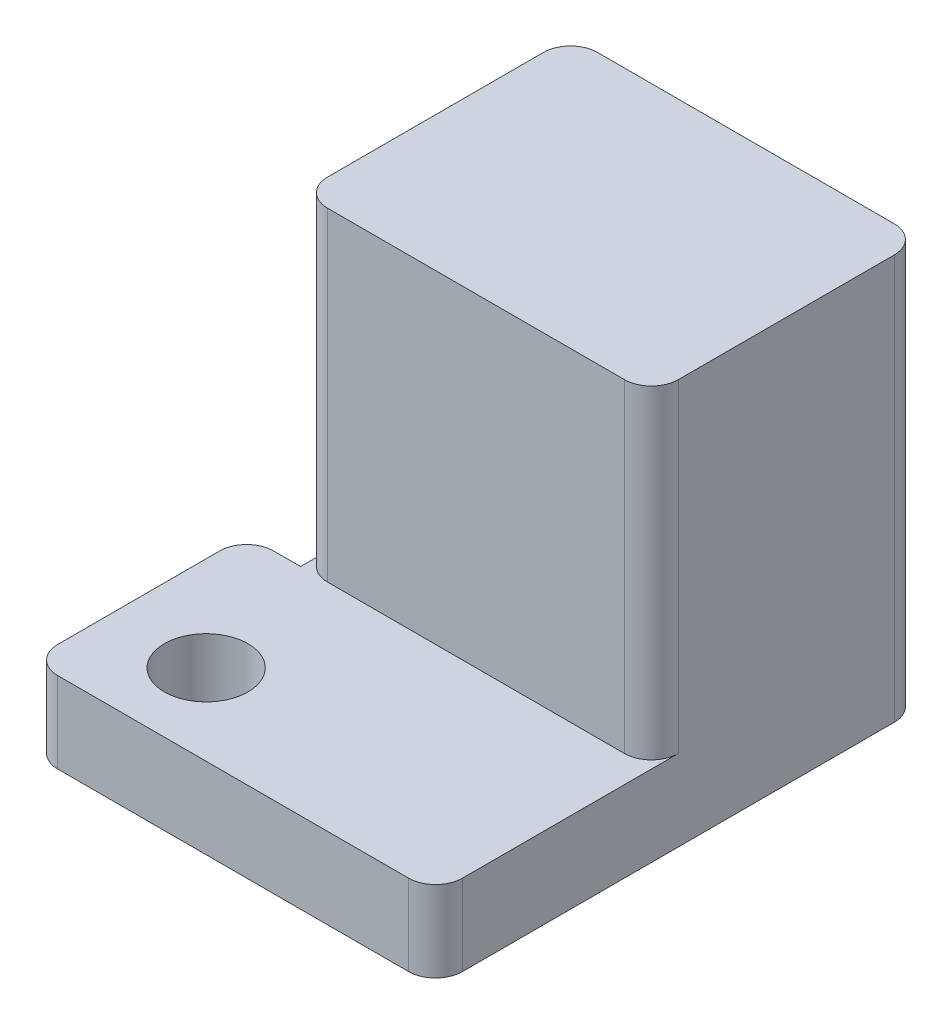
SolidWorks part; units mm, degrees
ref_plane "Alzado" through (0, 0, 0) normal (0, 0, 1) x (1, 0, 0)
ref_plane "Planta" through (0, 0, 0) normal (0, 1, 0) x (1, 0, 0)
ref_plane "Vista lateral" through (0, 0, 0) normal (1, 0, 0) x (0, 0, -1)
sketch "Croquis1" plane through (0, 0, 0) normal (0, 1, 0) x (1, 0, 0)
  line L0 (9, 18) -> (9, 0) construction
  line L1 (0, 0) -> (18, 0)
  line L2 (0, 0) -> (0, 18)
  line L3 (0, 18) -> (18, 18)
  line L4 (18, 0) -> (18, 18)
  circle A0 centre (3.5, 3) radius 1.55
  dimension "D3" = 3.1
  dimension "D4" = 3
  dimension "D5" = 3.5
  dimension "D1" = 18
  dimension "D2" = 18
extrude "Saliente-Extruir1" add sketch "Croquis1" along normal blind 3
sketch "Croquis3" plane through (0, 3, 0) normal (0, 1, 0) x (1, 0, 0)
  line L0 (18, 0) -> (18, 18) construction
  line L1 (0, 18) -> (18, 18)
  line L2 (0, 18) -> (0, 8)
  line L3 (0, 8) -> (18, 8)
  line L4 (18, 18) -> (18, 8)
  dimension "D1" = 10
extrude "Saliente-Extruir3" add sketch "Croquis3" along normal blind 3
sketch "Croquis4" plane through (0, 0, 0) normal (0, -1, 0) x (1, 0, 0)
  line L1 (0, -18) -> (2, -18)
  line L2 (0, -18) -> (0, -8)
  line L3 (0, -8) -> (2, -8)
  line L4 (2, -18) -> (2, -8)
  dimension "D1" = 10
  dimension "D2" = 2
extrude "Cortar-Extruir1" cut sketch "Croquis4" against normal up to surface (6 mm away) up to face at (9, 6, -13)
sketch "Croquis14" plane through (0, 6, 0) normal (0, 1, 0) x (1, 0, 0)
  line L4 (2, 18) -> (2, 8)
  line L5 (2, 8) -> (18, 8)
  line L6 (18, 8) -> (18, 18)
  line L7 (18, 18) -> (2, 18)
  line L8 (2, 18) -> (2, 8)
  line L9 (2, 8) -> (18, 8)
  line L10 (18, 8) -> (18, 18)
  line L11 (18, 18) -> (2, 18)
  dimension "D1" = 0
extrude "Saliente-Extruir8" add sketch "Croquis14" along normal blind 9
sketch "Croquis15" plane through (18, 0, 0) normal (1, 0, 0) x (0, 0, -1)
  line L6 (0, 0) -> (18, 0)
  line L7 (18, 0) -> (18, 15)
  line L8 (18, 15) -> (8, 15)
  line L9 (8, 15) -> (8, 3)
  line L10 (8, 3) -> (0, 3)
  line L11 (0, 3) -> (0, 0)
  line L12 (0, 0) -> (18, 0)
  line L13 (18, 0) -> (18, 15)
  line L14 (18, 15) -> (8, 15)
  line L15 (8, 15) -> (8, 3)
  line L16 (8, 3) -> (0, 3)
  line L17 (0, 3) -> (0, 0)
  dimension "D1" = 0
extrude "Cortar-Extruir2" cut sketch "Croquis15" against normal blind 3
fillet "Redondeo1" radius 1 7 edges at (2, 9, -8) (15, 9, -8) (0, 1.5, -8) (0, 1.5, 0) (15, 1.5, 0) (2, 7.5, -18) (15, 7.5, -18)
